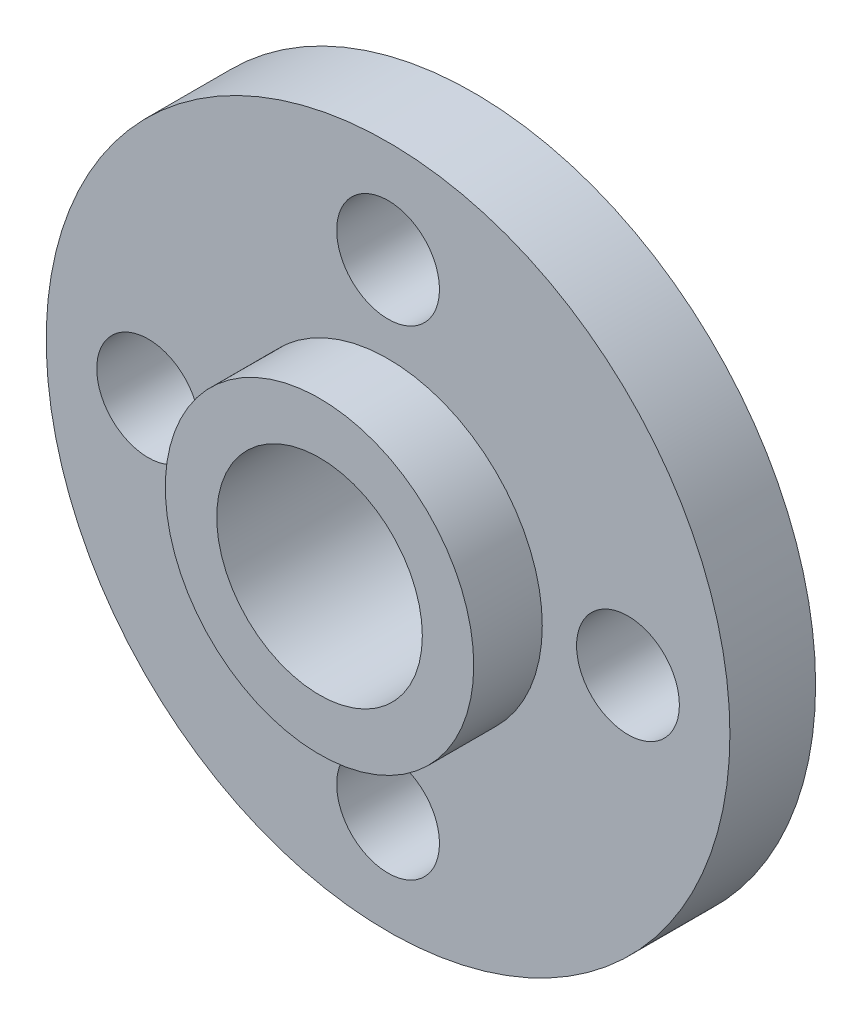
SolidWorks part; units mm, degrees
ref_plane "Front Plane" through (0, 0, 0) normal (0, 0, 1) x (1, 0, 0)
ref_plane "Top Plane" through (0, 0, 0) normal (0, 1, 0) x (1, 0, 0)
ref_plane "Right Plane" through (0, 0, 0) normal (1, 0, 0) x (0, 0, -1)
sketch "Sketch1" plane through (0, 0, 0) normal (0, 0, 1) x (1, 0, 0)
  circle A0 centre (0, 0) radius 9.975
  circle A1 centre (0, 0) radius 7 construction
  circle A2 centre (0, 7) radius 1.5
  circle A3 centre (7, 0) radius 1.5
  circle A4 centre (0, -7) radius 1.5
  circle A5 centre (-7, 0) radius 1.5
  point P15 (0, 0)
  dimension "D1" = 19.95
  dimension "D2" = 14
  dimension "D3" = 3
  dimension "D4" = 4
extrude "Boss-Extrude1" add sketch "Sketch1" along normal blind 2.5
sketch "Sketch2" plane through (0, 0, 2.5) normal (0, 0, 1) x (1, 0, 0)
  circle A0 centre (0, 0) radius 4.5
  dimension "D1" = 9
extrude "Boss-Extrude2" add sketch "Sketch2" along normal blind 2
sketch "Sketch3" plane through (0, 0, 4.5) normal (0, 0, 1) x (1, 0, 0)
  circle A0 centre (0, 0) radius 3
  dimension "D1" = 6
extrude "Cut-Extrude1" cut sketch "Sketch3" against normal through all
